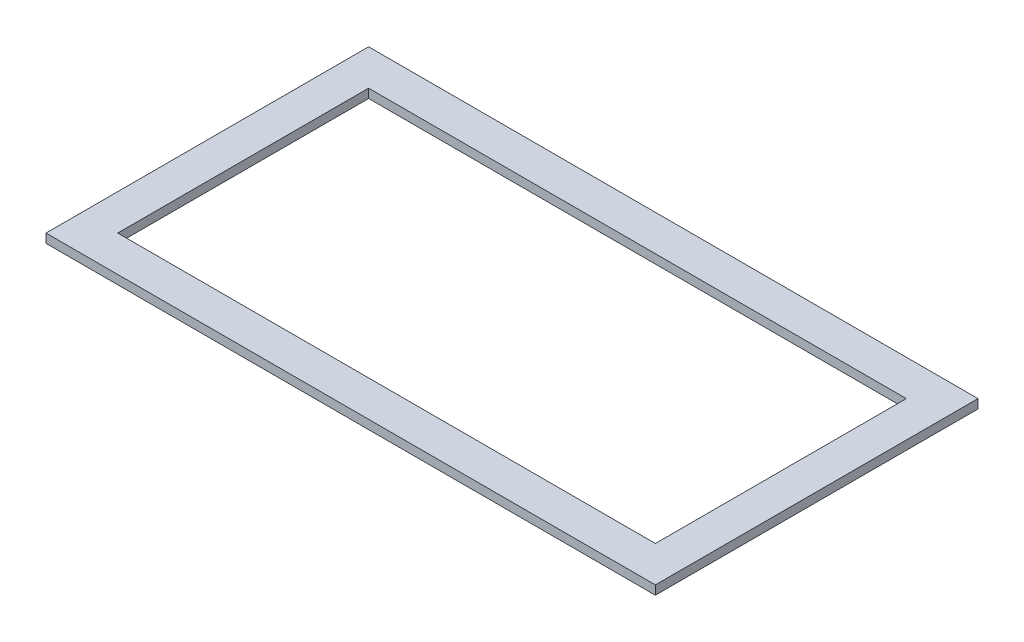
SolidWorks part; units mm, degrees
ref_plane "Front Plane" through (0, 0, 0) normal (0, 0, 1) x (1, 0, 0)
ref_plane "Top Plane" through (0, 0, 0) normal (0, 1, 0) x (1, 0, 0)
ref_plane "Right Plane" through (0, 0, 0) normal (1, 0, 0) x (0, 0, -1)
sketch "Sketch1" plane through (0, 0, 0) normal (0, 1, 0) x (1, 0, 0)
  line L1 (-107.95, -57.15) -> (107.95, -57.15)
  line L2 (-107.95, -57.15) -> (-107.95, 57.15)
  line L3 (-107.95, 57.15) -> (107.95, 57.15)
  line L4 (107.95, -57.15) -> (107.95, 57.15)
  line L5 (-107.95, -57.15) -> (107.95, 57.15) construction
  line L6 (-107.95, 57.15) -> (107.95, -57.15) construction
  point P0 (0, 0)
  dimension "D1" = 215.9
  dimension "D2" = 114.3
extrude "Boss-Extrude1" add sketch "Sketch1" along normal blind 3.175
sketch "Sketch2" plane through (0, 3.175, 0) normal (0, 1, 0) x (1, 0, 0)
  line L1 (-95.25, -44.45) -> (95.25, -44.45)
  line L2 (-95.25, -44.45) -> (-95.25, 44.45)
  line L3 (-95.25, 44.45) -> (95.25, 44.45)
  line L4 (95.25, -44.45) -> (95.25, 44.45)
  line L5 (-95.25, -44.45) -> (95.25, 44.45) construction
  line L6 (-95.25, 44.45) -> (95.25, -44.45) construction
  point P0 (0, 0)
  dimension "D1" = 190.5
  dimension "D2" = 88.9
extrude "Cut-Extrude1" cut sketch "Sketch2" against normal up to surface (3.175 mm away) up to face at (0, 0, 0)
